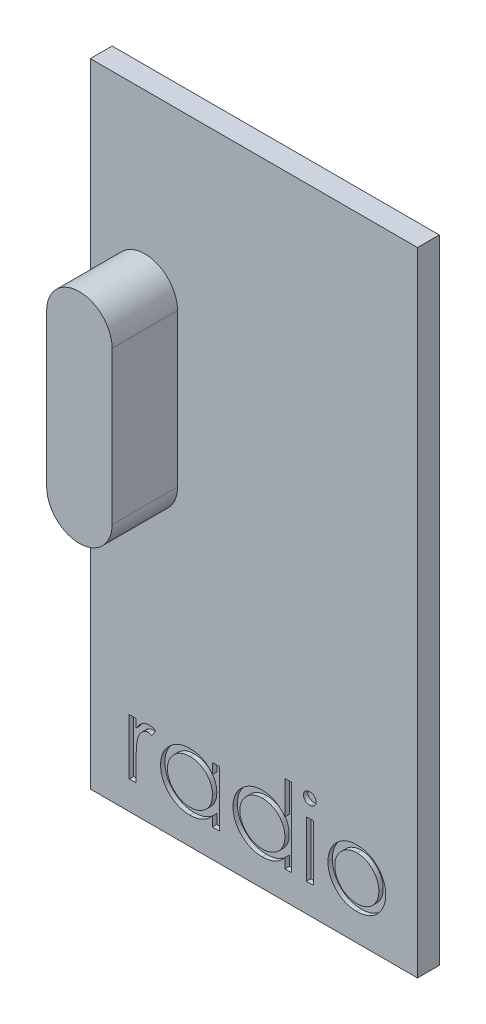
SolidWorks part; units mm, degrees
ref_plane "Front Plane" through (0, 0, 0) normal (0, 0, 1) x (1, 0, 0)
ref_plane "Top Plane" through (0, 0, 0) normal (0, 1, 0) x (1, 0, 0)
ref_plane "Right Plane" through (0, 0, 0) normal (1, 0, 0) x (0, 0, -1)
sketch "Sketch1" plane through (0, 0, 0) normal (0, 0, 1) x (1, 0, 0)
  line L1 (0, 0) -> (15, 0)
  line L2 (0, 0) -> (0, 29)
  line L3 (0, 29) -> (15, 29)
  line L4 (15, 0) -> (15, 29)
  dimension "D1" = 15
  dimension "D2" = 29
extrude "Boss-Extrude1" add sketch "Sketch1" along normal blind 1
sketch "Sketch2" plane through (0, 0, 1) normal (0, 0, 1) x (1, 0, 0)
  line L0 (0, 29) -> (0, 0) construction
  line L2 (1, 21) -> (1, 14)
  line L4 (4, 21) -> (4, 14)
  arc A0 (4, 21) -> (1, 21) centre (2.5, 21) ccw
  arc A1 (1, 14) -> (4, 14) centre (2.5, 14) ccw
  dimension "D1" = 1
  dimension "D2" = 7
  dimension "D4" = 3
extrude "Boss-Extrude2" add sketch "Sketch2" along normal blind 3
sketch "Sketch3" plane through (0, 0, 1) normal (0, 0, 1) x (1, 0, 0)
  text T0 "radio"
extrude "Cut-Extrude1" cut sketch "Sketch3" against normal blind 0.2
